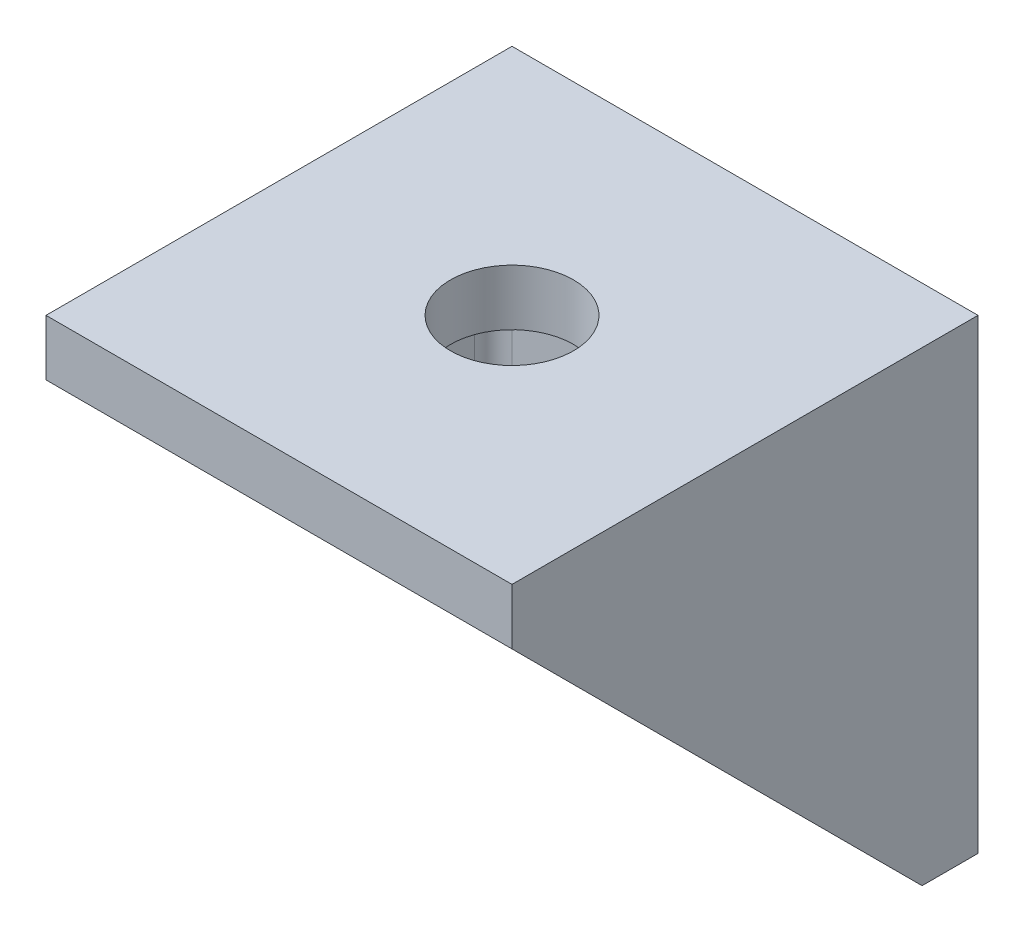
SolidWorks part; units mm, degrees
ref_plane "Front Plane" through (0, 0, 0) normal (0, 0, 1) x (1, 0, 0)
ref_plane "Top Plane" through (0, 0, 0) normal (0, 1, 0) x (1, 0, 0)
ref_plane "Right Plane" through (0, 0, 0) normal (1, 0, 0) x (0, 0, -1)
sketch "Sketch1" plane through (0, 0, 0) normal (0, 0, 1) x (1, 0, 0)
  line L1 (-12.5, -12.5) -> (12.5, -12.5)
  line L2 (-12.5, -12.5) -> (-12.5, 12.5)
  line L3 (-12.5, 12.5) -> (12.5, 12.5)
  line L4 (12.5, -12.5) -> (12.5, 12.5)
  line L5 (-12.5, -12.5) -> (12.5, 12.5) construction
  line L6 (-12.5, 12.5) -> (12.5, -12.5) construction
  point P0 (0, 0)
  dimension "D1" = 25
  dimension "D2" = 25
extrude "Boss-Extrude1" add sketch "Sketch1" along normal blind 3
sketch "Sketch2" plane through (0, 0, 3) normal (0, 0, 1) x (1, 0, 0)
  line L0 (12.5, -12.5) -> (12.5, 12.5) construction
  line L1 (-12.5, 12.5) -> (12.5, 12.5)
  line L2 (-12.5, 12.5) -> (-12.5, 9.5)
  line L3 (-12.5, 9.5) -> (12.5, 9.5)
  line L4 (12.5, 12.5) -> (12.5, 9.5)
  dimension "D1" = 3
extrude "Boss-Extrude2" add sketch "Sketch2" along normal blind 22
sketch "Sketch3" plane through (12.5, 0, 0) normal (1, 0, 0) x (0, 0, -1)
  line L0 (-25, 9.5) -> (-3, -12.5)
  line L1 (-3, -12.5) -> (-3, 9.5)
  line L2 (-3, 9.5) -> (-25, 9.5)
extrude "Boss-Extrude3" add sketch "Sketch3" against normal blind 2
sketch "Sketch4" plane through (-12.5, 0, 0) normal (-1, 0, 0) x (0, 0, 1)
  line L0 (3, -12.5) -> (3, 9.5)
  line L1 (3, 9.5) -> (25, 9.5)
  line L2 (25, 9.5) -> (3, -12.5)
extrude "Boss-Extrude4" add sketch "Sketch4" against normal blind 2
hole_wizard "M6 Clearance Hole1" positions "Sketch5" profile "Sketch6" hole size "M6" standard "ANSI Metric" end condition up to next
sketch "Sketch5" plane through (0, 9.5, 0) normal (0, -1, 0) x (-1, 0, 0)
  line L1 (10.5, -25) -> (-10.5, -25) construction
  line L2 (-12.5, -25) -> (-12.5, 0) construction
  point P0 (0, -12.5)
  point P9 (0, -25)
  point P15 (-12.5, -12.5)
sketch "Sketch6" plane through (0, 9.5, 12.5) normal (1, 0, 0) x (0, 0, -1)
  line L0 (0, 0) -> (0, 3)
  line L1 (0, 3) -> (3.3, 3)
  line L2 (3.3, 3) -> (3.3, 0)
  line L5 (3.3, 0) -> (0, 0)
  line L11 (0, -6.35) -> (0, 107.95) construction
  dimension "Thru Hole Dia." = 6.6
  dimension "Thru Hole Depth" = 3
hole_wizard "M6 Clearance Hole2" positions "Sketch9" profile "Sketch8" hole size "M6" standard "ANSI Metric" end condition up to next
sketch "Sketch9" plane through (0, 0, 3) normal (0, 0, 1) x (1, 0, 0)
  line L1 (-10.5, -12.5) -> (10.5, -12.5) construction
  line L2 (12.5, -12.5) -> (12.5, 12.5) construction
  point P0 (0, 0)
  point P9 (0, -12.5)
  point P14 (12.5, 0)
sketch "Sketch8" plane through (0, 0, 3) normal (1, 0, 0) x (0, -1, 0)
  line L0 (0, 0) -> (0, 3)
  line L1 (0, 3) -> (3.3, 3)
  line L2 (3.3, 3) -> (3.3, 0)
  line L5 (3.3, 0) -> (0, 0)
  line L11 (0, -6.35) -> (0, 107.95) construction
  dimension "Thru Hole Dia." = 6.6
  dimension "Thru Hole Depth" = 3
fillet "Fillet1" radius 1 5 edges at (-10.5, -1.5, 3) (-10.5, 9.5, 14) (10.5, 9.5, 14) (10.5, -1.5, 3) (0, 9.5, 3)
